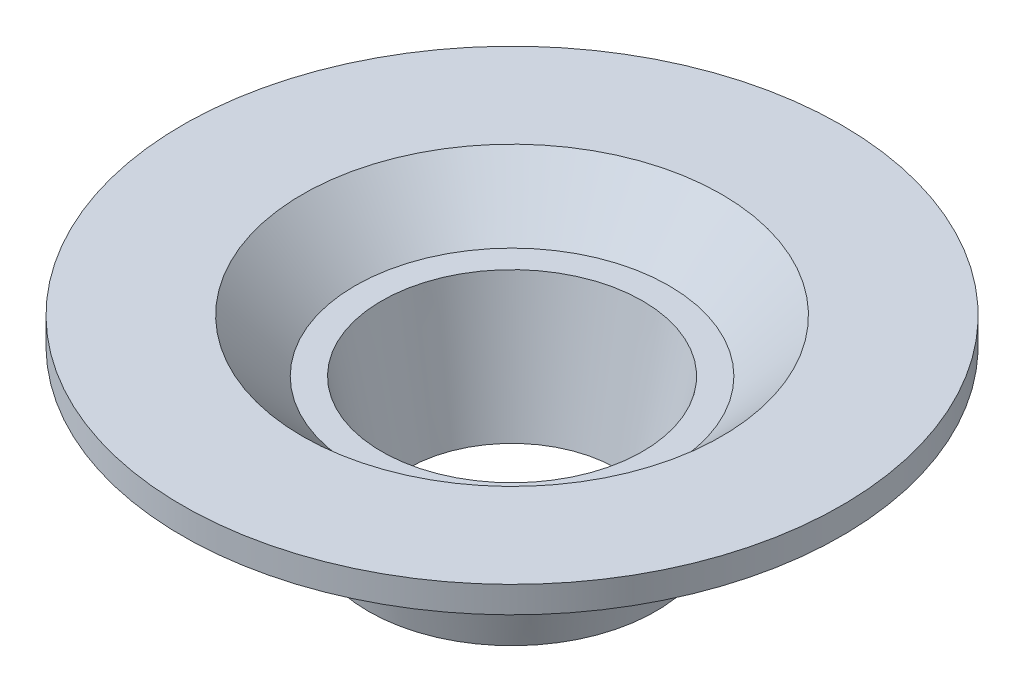
SolidWorks part; units mm, degrees
material "Titanium"
ref_plane "Front Plane" through (0, 0, 0) normal (0, 0, 1) x (1, 0, 0)
ref_plane "Top Plane" through (0, 0, 0) normal (0, 1, 0) x (1, 0, 0)
ref_plane "Right Plane" through (0, 0, 0) normal (1, 0, 0) x (0, 0, -1)
sketch "Sketch1" plane through (0, 0, 0) normal (0, 0, 1) x (1, 0, 0)
  line L0 (0, 0) -> (0, 5) construction
  line L5 (4.95, 5) -> (5.95, 5)
  line L6 (5.95, 5) -> (7.95, 7)
  line L7 (7.95, 7) -> (12.5, 7)
  line L8 (12.5, 7) -> (12.5, 6)
  line L9 (12.5, 6) -> (10.5, 6)
  line L10 (10.5, 6) -> (8.5, 4)
  line L11 (8.5, 4) -> (6.25, 4)
  line L12 (6.25, 4) -> (5.45, 0)
  line L13 (5.45, 0) -> (3.95, 0)
  line L14 (3.95, 0) -> (4.95, 5)
  dimension "D2" = 5
  dimension "D3" = 25
  dimension "D4" = 2
  dimension "D5" = 2
  dimension "D6" = 1
  dimension "D7" = 2
  dimension "D8" = 4
  dimension "D9" = 12.5
  dimension "D10" = 1.5
  dimension "D11" = 9.9
  dimension "D12" = 1
  dimension "D13" = 7.9
revolve "Revolve1" add sketch "Sketch1" angle 360 about L0
